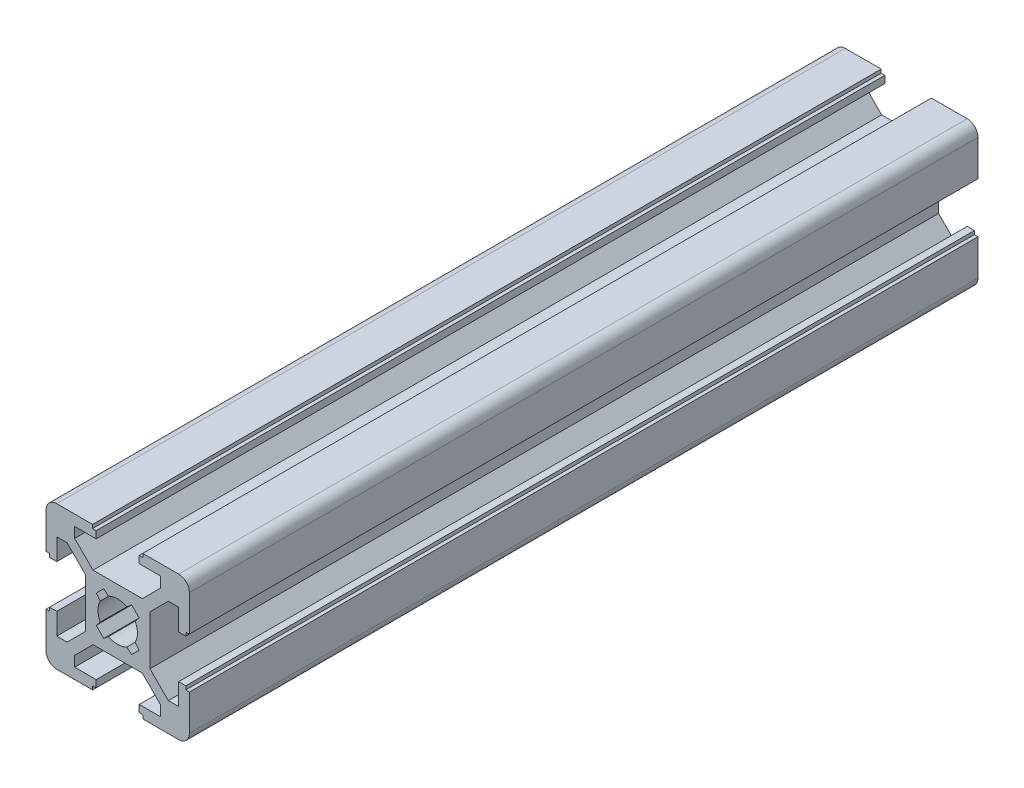
SolidWorks part; units mm, degrees
ref_plane "Ebene vorne" through (0, 0, 0) normal (0, 0, 1) x (1, 0, 0)
ref_plane "Ebene oben" through (0, 0, 0) normal (0, 1, 0) x (1, 0, 0)
ref_plane "Ebene rechts" through (0, 0, 0) normal (1, 0, 0) x (0, 0, -1)
sketch "Skizze1" plane through (0, 0, 0) normal (0, 0, 1) x (1, 0, 0)
  line L0 (-2.539, 1.0906) -> (-3.1036, 1.7634)
  line L1 (-3.1036, -2.1357) -> (-2.539, -1.4629)
  line L2 (-2.053, -3.1863) -> (-3.1036, -2.1357)
  line L3 (-1.3802, -2.6218) -> (-2.053, -3.1863)
  line L4 (1.8462, -3.1863) -> (1.1734, -2.6218)
  line L5 (2.8968, -2.1357) -> (1.8462, -3.1863)
  line L6 (2.3323, -1.4629) -> (2.8968, -2.1357)
  line L7 (2.8968, 1.7634) -> (2.3323, 1.0906)
  line L8 (1.8462, 2.814) -> (2.8968, 1.7634)
  line L9 (1.1734, 2.2495) -> (1.8462, 2.814)
  line L10 (-2.053, 2.814) -> (-1.3802, 2.2495)
  line L11 (-3.1036, 1.7634) -> (-2.053, 2.814)
  line L12 (9.8966, -8.6862) -> (9.8966, -3.6862)
  line L13 (9.8966, -3.6862) -> (9.3966, -3.6862)
  line L14 (9.3966, -3.6862) -> (9.3966, -3.1862)
  line L15 (9.3966, -3.1862) -> (8.3966, -3.1862)
  line L16 (8.3966, -3.1862) -> (8.3966, -6.1862)
  line L17 (8.3966, -6.1862) -> (6.9573, -6.1862)
  line L18 (6.9573, -6.1862) -> (4.3966, -3.6255)
  line L19 (4.3966, -3.6255) -> (4.3966, 3.2532)
  line L20 (4.3966, 3.2532) -> (6.9573, 5.8138)
  line L21 (6.9573, 5.8138) -> (8.3966, 5.8138)
  line L22 (8.3966, 5.8138) -> (8.3966, 2.8138)
  line L23 (8.3966, 2.8138) -> (9.3966, 2.8138)
  line L24 (9.3966, 2.8138) -> (9.3966, 3.3138)
  line L25 (9.3966, 3.3138) -> (9.8966, 3.3138)
  line L26 (9.8966, 3.3138) -> (9.8966, 8.3138)
  line L27 (8.3966, 9.8138) -> (3.3966, 9.8138)
  line L28 (3.3966, 9.8138) -> (3.3966, 9.3138)
  line L29 (3.3966, 9.3138) -> (2.8966, 9.3138)
  line L30 (2.8966, 9.3138) -> (2.8966, 8.3138)
  line L31 (2.8966, 8.3138) -> (5.8966, 8.3138)
  line L32 (5.8966, 8.3138) -> (5.8966, 6.8745)
  line L33 (5.8966, 6.8745) -> (3.336, 4.3138)
  line L34 (3.336, 4.3138) -> (-3.5427, 4.3138)
  line L35 (-3.5427, 4.3138) -> (-6.1034, 6.8745)
  line L36 (-6.1034, 6.8745) -> (-6.1034, 8.3138)
  line L37 (-6.1034, 8.3138) -> (-3.1034, 8.3138)
  line L38 (-3.1034, 8.3138) -> (-3.1034, 9.3138)
  line L39 (-3.1034, 9.3138) -> (-3.6034, 9.3138)
  line L40 (-3.6034, 9.3138) -> (-3.6034, 9.8138)
  line L41 (-3.6034, 9.8138) -> (-8.6034, 9.8138)
  line L42 (-10.1034, 8.3138) -> (-10.1034, 3.3138)
  line L43 (-10.1034, 3.3138) -> (-9.6034, 3.3138)
  line L44 (-9.6034, 3.3138) -> (-9.6034, 2.8138)
  line L45 (-9.6034, 2.8138) -> (-8.6034, 2.8138)
  line L46 (-8.6034, 2.8138) -> (-8.6034, 5.8138)
  line L47 (-8.6034, 5.8138) -> (-7.164, 5.8138)
  line L48 (-7.164, 5.8138) -> (-4.6034, 3.2532)
  line L49 (-4.6034, 3.2532) -> (-4.6034, -3.6255)
  line L50 (-4.6034, -3.6255) -> (-7.164, -6.1862)
  line L51 (-7.164, -6.1862) -> (-8.6034, -6.1862)
  line L52 (-8.6034, -6.1862) -> (-8.6034, -3.1862)
  line L53 (-8.6034, -3.1862) -> (-9.6034, -3.1862)
  line L54 (-9.6034, -3.1862) -> (-9.6034, -3.6862)
  line L55 (-9.6034, -3.6862) -> (-10.1034, -3.6862)
  line L56 (-10.1034, -3.6862) -> (-10.1034, -8.6862)
  line L57 (-8.6034, -10.1862) -> (-3.6034, -10.1862)
  line L58 (-3.6034, -10.1862) -> (-3.6034, -9.6862)
  line L59 (-3.6034, -9.6862) -> (-3.1034, -9.6862)
  line L60 (-3.1034, -9.6862) -> (-3.1034, -8.6862)
  line L61 (-3.1034, -8.6862) -> (-6.1034, -8.6862)
  line L62 (-6.1034, -8.6862) -> (-6.1034, -7.2468)
  line L63 (-6.1034, -7.2468) -> (-3.5427, -4.6862)
  line L64 (-3.5427, -4.6862) -> (3.336, -4.6862)
  line L65 (3.336, -4.6862) -> (5.8966, -7.2468)
  line L66 (5.8966, -7.2468) -> (5.8966, -8.6862)
  line L67 (5.8966, -8.6862) -> (2.8966, -8.6862)
  line L68 (2.8966, -8.6862) -> (2.8966, -9.6862)
  line L69 (2.8966, -9.6862) -> (3.3966, -9.6862)
  line L70 (3.3966, -9.6862) -> (3.3966, -10.1862)
  line L71 (3.3966, -10.1862) -> (8.3966, -10.1862)
  arc A0 (8.3966, -10.1862) -> (9.8966, -8.6862) centre (8.3966, -8.6862) ccw
  arc A1 (9.8966, 8.3138) -> (8.3966, 9.8138) centre (8.3966, 8.3138) ccw
  arc A2 (-8.6034, 9.8138) -> (-10.1034, 8.3138) centre (-8.6034, 8.3138) ccw
  arc A3 (-10.1034, -8.6862) -> (-8.6034, -10.1862) centre (-8.6034, -8.6862) ccw
  arc A4 (-2.539, 1.0906) -> (-2.539, -1.4629) centre (-0.1034, -0.1862) ccw
  arc A5 (-1.3802, -2.6218) -> (1.1734, -2.6218) centre (-0.1034, -0.1862) ccw
  arc A6 (2.3323, -1.4629) -> (2.3323, 1.0906) centre (-0.1034, -0.1862) ccw
  arc A7 (1.1734, 2.2495) -> (-1.3802, 2.2495) centre (-0.1034, -0.1862) ccw
extrude "Aufsatz-Linear austragen1" add sketch "Skizze1" along normal blind 110
